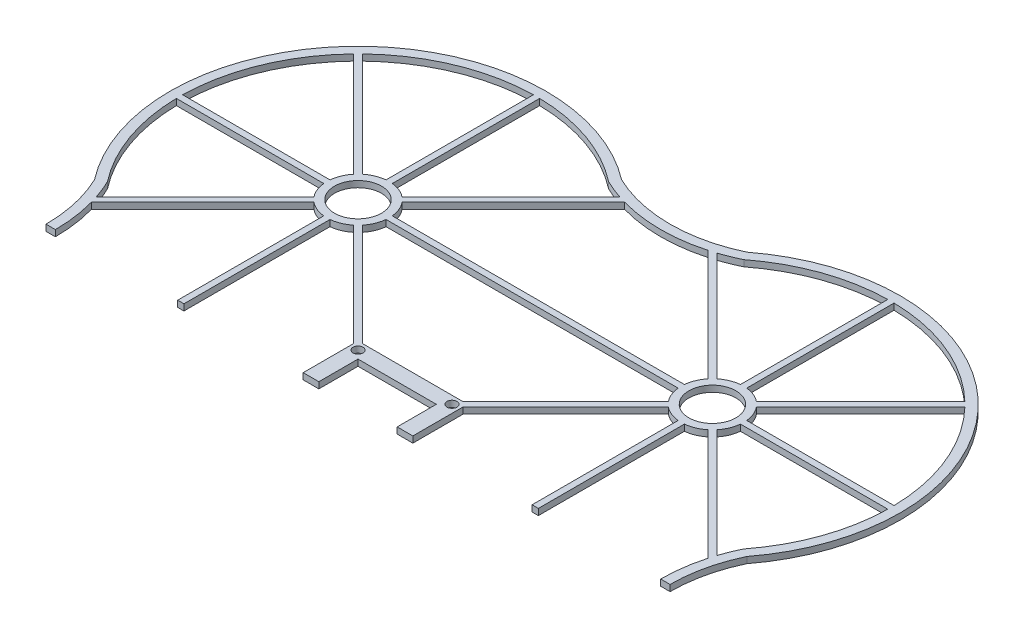
SolidWorks part; units mm, degrees
ref_plane "Front Plane" through (0, 0, 0) normal (0, 0, 1) x (1, 0, 0)
ref_plane "Top Plane" through (0, 0, 0) normal (0, 1, 0) x (1, 0, 0)
ref_plane "Right Plane" through (0, 0, 0) normal (1, 0, 0) x (0, 0, -1)
sketch "Sketch1" plane through (0, 0, 0) normal (0, 1, 0) x (1, 0, 0)
  line L0 (14.1421, 14.1421) -> (15, 15)
  line L1 (-15, -15) -> (-13.3013, -15)
  line L2 (-15, -15) -> (-15, -13.3013)
  line L3 (-15, 15) -> (-13.3013, 15) construction
  line L4 (15, -15) -> (15, -13.3013)
  line L5 (-15, -15) -> (-14.1421, -14.1421) construction
  line L6 (-15, 15) -> (-14.1421, 14.1421) construction
  line L7 (14.1421, -14.1421) -> (15, -15)
  line L8 (-14.1421, -14.1421) -> (-15, -15)
  line L9 (-14.1421, 14.1421) -> (-56.5685, 56.5685)
  line L10 (-104.1368, 20) -> (-104.1368, -20) construction
  line L11 (15, -15) -> (56.5685, -56.5685) construction
  line L12 (-15, -15) -> (-56.5685, -56.5685) construction
  line L13 (15, 15) -> (56.5685, 56.5685) construction
  line L14 (-13.3013, 15) -> (13.3013, 15) construction
  line L15 (13.3013, 15) -> (15, 15)
  line L16 (-14.1421, 14.1421) -> (0, 0) construction
  line L17 (14.1421, -14.1421) -> (15, -15) construction
  line L18 (0, 0) -> (-14.1421, 14.1421) construction
  line L19 (-15, -13.3013) -> (-15, 13.3013) construction
  line L20 (-15, 13.3013) -> (-15, 15)
  line L21 (-14.1421, -14.1421) -> (0, 0) construction
  line L22 (14.1421, 14.1421) -> (15, 15) construction
  line L23 (0, 0) -> (-14.1421, -14.1421) construction
  line L24 (-13.3013, -15) -> (13.3013, -15) construction
  line L25 (13.3013, -15) -> (15, -15)
  line L26 (0, 0) -> (14.1421, -14.1421) construction
  line L27 (0, 0) -> (14.1421, -14.1421) construction
  line L28 (15, -13.3013) -> (15, 13.3013) construction
  line L29 (15, 13.3013) -> (15, 15)
  line L30 (0, 0) -> (14.1421, 14.1421) construction
  line L31 (0, 0) -> (14.1421, 14.1421) construction
  arc A0 (13.3013, 15) -> (15, 13.3013) centre (56.5685, 56.5685) ccw
  arc A1 (76.5685, 0) -> (36.5685, 0) centre (56.5685, -56.5685) ccw construction
  arc A2 (-104.1368, -20) -> (-20, -104.1368) centre (-56.5685, -56.5685) ccw
  arc A3 (-15, 13.3013) -> (-14.1421, 14.1421) centre (-56.5685, 56.5685) ccw
  arc A4 (-104.1368, 20) -> (-104.1368, -20) centre (-146.0012, 0) cw
  arc A5 (20, 104.1368) -> (-20, 104.1368) centre (0, 146.0012) cw
  arc A6 (104.1368, -20) -> (104.1368, 20) centre (146.0012, 0) cw
  arc A7 (-20, -104.1368) -> (20, -104.1368) centre (0, -146.0012) cw
  arc A8 (-76.5685, 0) -> (-36.5685, 0) centre (-56.5685, 56.5685) ccw construction
  arc A9 (-36.5685, 0) -> (-76.5685, 0) centre (-56.5685, -56.5685) ccw construction
  arc A10 (-76.5685, 0) -> (-104.1368, -20) centre (-56.5685, -56.5685) ccw construction
  arc A11 (-104.1368, 20) -> (-76.5685, 0) centre (-56.5685, 56.5685) ccw construction
  arc A12 (0, 76.5685) -> (-20, 104.1368) centre (-56.5685, 56.5685) ccw construction
  arc A13 (-20, 104.1368) -> (-104.1368, 20) centre (-56.5685, 56.5685) ccw
  arc A14 (20, 104.1368) -> (0, 76.5685) centre (56.5685, 56.5685) ccw construction
  arc A15 (0, 36.5685) -> (0, 76.5685) centre (-56.5685, 56.5685) ccw construction
  arc A16 (0, 76.5685) -> (0, 36.5685) centre (56.5685, 56.5685) ccw construction
  arc A17 (76.5685, 0) -> (104.1368, 20) centre (56.5685, 56.5685) ccw construction
  arc A18 (104.1368, 20) -> (20, 104.1368) centre (56.5685, 56.5685) ccw
  arc A19 (104.1368, -20) -> (76.5685, 0) centre (56.5685, -56.5685) ccw construction
  arc A20 (0, -76.5685) -> (20, -104.1368) centre (56.5685, -56.5685) ccw construction
  arc A21 (20, -104.1368) -> (104.1368, -20) centre (56.5685, -56.5685) ccw
  arc A22 (-20, -104.1368) -> (0, -76.5685) centre (-56.5685, -56.5685) ccw construction
  arc A23 (-13.3013, -15) -> (-15, -13.3013) centre (-56.5685, -56.5685) ccw
  arc A24 (0, -36.5685) -> (0, -76.5685) centre (56.5685, -56.5685) ccw construction
  arc A25 (0, -76.5685) -> (0, -36.5685) centre (-56.5685, -56.5685) ccw construction
  arc A26 (13.3013, -15) -> (0, -36.5685) centre (56.5685, -56.5685) ccw construction
  arc A27 (0, -36.5685) -> (-13.3013, -15) centre (-56.5685, -56.5685) ccw construction
  arc A28 (-15, -13.3013) -> (-36.5685, 0) centre (-56.5685, -56.5685) ccw construction
  arc A29 (-36.5685, 0) -> (-15, 13.3013) centre (-56.5685, 56.5685) ccw construction
  arc A30 (36.5685, 0) -> (15, -13.3013) centre (56.5685, -56.5685) ccw construction
  arc A31 (15, -13.3013) -> (13.3013, -15) centre (56.5685, -56.5685) ccw
  arc A32 (15, 13.3013) -> (36.5685, 0) centre (56.5685, 56.5685) ccw construction
  arc A33 (36.5685, 0) -> (76.5685, 0) centre (56.5685, 56.5685) ccw construction
  arc A34 (0, 36.5685) -> (13.3013, 15) centre (56.5685, 56.5685) ccw construction
  arc A35 (-14.1421, 14.1421) -> (-13.3013, 15) centre (-56.5685, 56.5685) ccw construction
  arc A36 (-13.3013, 15) -> (0, 36.5685) centre (-56.5685, 56.5685) ccw construction
  arc A37 (-21.5857, 101.5708) -> (-101.5708, 21.5857) centre (-56.5685, 56.5685) ccw
  arc A38 (-101.5708, 21.5857) -> (-101.5708, -21.5857) centre (-146.0012, 0) cw
  arc A39 (-101.5708, -21.5857) -> (-21.5857, -101.5708) centre (-56.5685, -56.5685) ccw
  arc A40 (-21.5857, -101.5708) -> (21.5857, -101.5708) centre (0, -146.0012) cw
  arc A41 (21.5857, -101.5708) -> (101.5708, -21.5857) centre (56.5685, -56.5685) ccw
  arc A42 (101.5708, -21.5857) -> (101.5708, 21.5857) centre (146.0012, 0) cw
  arc A43 (101.5708, 21.5857) -> (21.5857, 101.5708) centre (56.5685, 56.5685) ccw
  arc A44 (21.5857, 101.5708) -> (-21.5857, 101.5708) centre (0, 146.0012) cw
  point P0 (0, 0)
  point P18 (0, 0)
  point P31 (0, 0)
  point P45 (-266.1251, 102.6457)
  dimension "D1" = 3
  dimension "D7" = 4
extrude "Boss-Extrude1" add sketch "Sketch1" along normal blind 2 contours A7 A21 A6 A18 A5 A13 A4 A2 A44 A43 A42 A41 A40 A39 A38 A37
sketch "Sketch2" plane through (0, 2, 0) normal (0, 1, 0) x (1, 0, 0)
  line L0 (-96.8736, 96.8736) -> (-63.6396, 63.6396)
  line L1 (-15, 15) -> (-13.4, 15)
  line L2 (-15, 15) -> (-15, 13.4)
  line L3 (-15, -15) -> (-13.4, -15)
  line L4 (15, 15) -> (15, 13.4)
  line L5 (-15, 15) -> (15, -15) construction
  line L6 (-15, -15) -> (15, 15) construction
  line L7 (16.0858, -17.5) -> (-16.0858, -17.5)
  line L8 (17.5, -16.0858) -> (17.5, 16.0858)
  line L9 (16.0858, 17.5) -> (-16.0858, 17.5)
  line L10 (-17.5, -16.0858) -> (-17.5, 16.0858)
  line L11 (16.1314, -16.1314) -> (-17.5, 17.5) construction
  line L12 (17.5, 17.5) -> (-17.5, -17.5) construction
  line L13 (12.5, -12.5) -> (-12.5, -12.5)
  line L14 (12.5, -12.5) -> (12.5, 12.5)
  line L15 (12.5, 12.5) -> (-12.5, 12.5)
  line L16 (-12.5, -12.5) -> (-12.5, 12.5)
  line L17 (12.5, -12.5) -> (-12.5, 12.5) construction
  line L18 (12.5, 12.5) -> (-12.5, -12.5) construction
  line L19 (-97.5807, 96.1665) -> (-64.3113, 62.8971)
  line L20 (-96.1665, 97.5807) -> (-62.8971, 64.3113)
  line L21 (-57.5685, 113.5685) -> (-57.5685, 66.5184)
  line L22 (-55.5685, 113.5685) -> (-55.5685, 66.5184)
  line L23 (-15.4636, 99.0877) -> (-50.24, 64.3113)
  line L24 (-13.2952, 98.4277) -> (-48.8258, 62.8971)
  line L25 (0.4315, 57.5685) -> (-46.6187, 57.5685)
  line L26 (0.4315, 55.5685) -> (-46.6187, 55.5685)
  line L27 (-16.0858, 17.5) -> (-48.8258, 50.24)
  line L28 (-17.5, 16.0858) -> (-50.24, 48.8258)
  line L29 (-55.5685, -46.6187) -> (-55.5685, 46.6187)
  line L30 (-57.5685, -46.6187) -> (-57.5685, 46.6187)
  line L31 (-98.4277, 13.2952) -> (-62.8971, 48.8258)
  line L32 (-99.0877, 15.4636) -> (-64.3113, 50.24)
  line L33 (-113.5685, 55.5685) -> (-66.5184, 55.5685)
  line L34 (-113.5685, 57.5685) -> (-66.5184, 57.5685)
  line L35 (55.5685, 113.5685) -> (55.5685, 66.5184)
  line L36 (57.5685, 113.5685) -> (57.5685, 66.5184)
  line L37 (96.1665, 97.5807) -> (62.8971, 64.3113)
  line L38 (97.5807, 96.1665) -> (64.3113, 62.8971)
  line L39 (113.5685, 57.5685) -> (66.5184, 57.5685)
  line L40 (113.5685, 55.5685) -> (66.5184, 55.5685)
  line L41 (99.0877, 15.4636) -> (64.3113, 50.24)
  line L42 (98.4277, 13.2952) -> (62.8971, 48.8258)
  line L43 (15.4636, 99.0877) -> (50.24, 64.3113)
  line L44 (13.2952, 98.4277) -> (48.8258, 62.8971)
  line L45 (-46.5685, 57.5685) -> (46.6187, 57.5685)
  line L46 (-46.5685, 55.5685) -> (46.6187, 55.5685)
  line L47 (16.0858, 17.5) -> (48.8258, 50.24)
  line L48 (17.5, 16.0858) -> (50.24, 48.8258)
  line L49 (55.5685, -46.6187) -> (55.5685, 46.6187)
  line L50 (57.5685, -46.6187) -> (57.5685, 46.6187)
  line L51 (113.5685, -55.5685) -> (66.5184, -55.5685)
  line L52 (113.5685, -57.5685) -> (66.5184, -57.5685)
  line L53 (97.5807, -96.1665) -> (64.3113, -62.8971)
  line L54 (96.1665, -97.5807) -> (62.8971, -64.3113)
  line L55 (57.5685, -113.5685) -> (57.5685, -66.5184)
  line L56 (55.5685, -113.5685) -> (55.5685, -66.5184)
  line L57 (15.4636, -99.0877) -> (50.24, -64.3113)
  line L58 (13.2952, -98.4277) -> (48.8258, -62.8971)
  line L59 (99.0877, -15.4636) -> (64.3113, -50.24)
  line L60 (98.4277, -13.2952) -> (62.8971, -48.8258)
  line L61 (57.5685, 0.4315) -> (57.5685, -46.5685)
  line L62 (55.5685, 0.4315) -> (55.5685, -46.5685)
  line L63 (17.5, -16.0858) -> (50.24, -48.8258)
  line L64 (16.0858, -17.5) -> (48.8258, -50.24)
  line L65 (-46.6187, -55.5685) -> (46.6187, -55.5685)
  line L66 (-46.6187, -57.5685) -> (46.6187, -57.5685)
  line L67 (-55.5685, -113.5685) -> (-55.5685, -66.5184)
  line L68 (-57.5685, -113.5685) -> (-57.5685, -66.5184)
  line L69 (-96.1665, -97.5807) -> (-62.8971, -64.3113)
  line L70 (-97.5807, -96.1665) -> (-64.3113, -62.8971)
  line L71 (-113.5685, -57.5685) -> (-66.5184, -57.5685)
  line L72 (-113.5685, -55.5685) -> (-66.5184, -55.5685)
  line L73 (-99.0877, -15.4636) -> (-64.3113, -50.24)
  line L74 (-98.4277, -13.2952) -> (-62.8971, -48.8258)
  line L75 (-15.4636, -99.0877) -> (-50.24, -64.3113)
  line L76 (-13.2952, -98.4277) -> (-48.8258, -62.8971)
  line L77 (0.4315, -57.5685) -> (-46.5685, -57.5685)
  line L78 (0.4315, -55.5685) -> (-46.5685, -55.5685)
  line L79 (-16.0858, -17.5) -> (-48.8258, -50.24)
  line L80 (-17.5, -16.0858) -> (-50.24, -48.8258)
  line L81 (-55.5685, 0.4315) -> (-55.5685, -46.5685)
  line L82 (-57.5685, 0.4315) -> (-57.5685, -46.5685)
  line L83 (-97.5807, 96.1665) -> (-64.3467, 62.9325) construction
  line L84 (-96.1665, 97.5807) -> (-62.9325, 64.3467) construction
  line L85 (13.4, -15) -> (15, -15)
  line L86 (15, -13.4) -> (15, -15)
  line L87 (13.4, 15) -> (15, 15)
  line L88 (-15, -13.4) -> (-15, -15)
  circle A0 centre (-15, 15) radius 1.6
  circle A1 centre (15, 15) radius 1.6
  circle A2 centre (15, -15) radius 1.6
  circle A3 centre (-15, -15) radius 1.6
  arc A4 (-62.8971, 48.8258) -> (-57.5685, 46.6187) centre (-56.5685, 56.5685) ccw
  arc A5 (-21.5857, 101.5708) -> (-101.5708, 21.5857) centre (-56.5685, 56.5685) ccw construction
  arc A6 (-21.5857, 101.5708) -> (-55.5685, 113.5598) centre (-56.5685, 56.5685) ccw
  arc A7 (50.24, 48.8258) -> (55.5685, 46.6187) centre (56.5685, 56.5685) ccw
  arc A8 (57.5685, -66.5184) -> (62.8971, -64.3113) centre (56.5685, -56.5685) ccw
  arc A9 (-62.8971, -64.3113) -> (-57.5685, -66.5184) centre (-56.5685, -56.5685) ccw
  arc A10 (-21.5857, 101.5708) -> (21.5857, 101.5708) centre (0, 146.0012) ccw construction
  arc A11 (101.5708, 21.5857) -> (21.5857, 101.5708) centre (56.5685, 56.5685) ccw construction
  arc A12 (101.5708, 21.5857) -> (101.5708, -21.5857) centre (146.0012, 0) ccw construction
  arc A13 (21.5857, -101.5708) -> (101.5708, -21.5857) centre (56.5685, -56.5685) ccw construction
  arc A14 (21.5857, -101.5708) -> (-21.5857, -101.5708) centre (0, -146.0012) ccw construction
  arc A15 (-101.5708, -21.5857) -> (-21.5857, -101.5708) centre (-56.5685, -56.5685) ccw construction
  arc A16 (-101.5708, -21.5857) -> (-101.5708, 21.5857) centre (-146.0012, 0) ccw construction
  arc A17 (-21.5857, 101.5708) -> (-15.4636, 99.0877) centre (0, 146.0012) ccw
  arc A18 (20, -104.1368) -> (-20, -104.1368) centre (0, -146.0012) ccw
  arc A19 (20, -104.1368) -> (104.1368, -20) centre (56.5685, -56.5685) ccw
  arc A20 (104.1368, 20) -> (104.1368, -20) centre (146.0012, 0) ccw
  arc A21 (104.1368, 20) -> (20, 104.1368) centre (56.5685, 56.5685) ccw
  arc A22 (-20, 104.1368) -> (20, 104.1368) centre (0, 146.0012) ccw
  arc A23 (-20, 104.1368) -> (-104.1368, 20) centre (-56.5685, 56.5685) ccw
  arc A24 (-104.1368, -20) -> (-104.1368, 20) centre (-146.0012, 0) ccw
  arc A25 (-104.1368, -20) -> (-20, -104.1368) centre (-56.5685, -56.5685) ccw
  arc A26 (20, -104.1368) -> (-20, -104.1368) centre (0, -146.0012) ccw
  arc A27 (20, -104.1368) -> (104.1368, -20) centre (56.5685, -56.5685) ccw
  arc A28 (104.1368, 20) -> (104.1368, -20) centre (146.0012, 0) ccw
  arc A29 (104.1368, 20) -> (20, 104.1368) centre (56.5685, 56.5685) ccw
  arc A30 (-20, 104.1368) -> (20, 104.1368) centre (0, 146.0012) ccw
  arc A31 (-20, 104.1368) -> (-104.1368, 20) centre (-56.5685, 56.5685) ccw
  arc A32 (-104.1368, -20) -> (-104.1368, 20) centre (-146.0012, 0) ccw
  arc A33 (-104.1368, -20) -> (-20, -104.1368) centre (-56.5685, -56.5685) ccw
  arc A34 (101.5708, 21.5857) -> (113.5598, 55.5685) centre (56.5685, 56.5685) ccw
  arc A35 (101.5708, 21.5857) -> (99.0877, 15.4636) centre (146.0012, 0) ccw
  arc A36 (21.5857, -101.5708) -> (55.5685, -113.5598) centre (56.5685, -56.5685) ccw
  arc A37 (21.5857, -101.5708) -> (15.4636, -99.0877) centre (0, -146.0012) ccw
  arc A38 (-101.5708, -21.5857) -> (-113.5598, -55.5685) centre (-56.5685, -56.5685) ccw
  arc A39 (-101.5708, -21.5857) -> (-99.0877, -15.4636) centre (-146.0012, 0) ccw
  circle A40 centre (-56.5685, -56.5685) radius 7.5
  circle A41 centre (-56.5685, 56.5685) radius 7.5
  circle A42 centre (56.5685, 56.5685) radius 7.5
  circle A43 centre (56.5685, -56.5685) radius 7.5
  arc A44 (57.5685, -113.5598) -> (96.1603, -97.5745) centre (56.5685, -56.5685) ccw
  arc A45 (13.2952, -98.4277) -> (-13.2952, -98.4277) centre (0, -146.0012) ccw
  arc A46 (97.5745, -96.1603) -> (113.5598, -57.5685) centre (56.5685, -56.5685) ccw
  arc A47 (-15.4636, -99.0877) -> (-21.5857, -101.5708) centre (0, -146.0012) ccw
  arc A48 (48.8258, -50.24) -> (46.6187, -55.5685) centre (56.5685, -56.5685) ccw
  arc A49 (55.5685, -46.6187) -> (50.24, -48.8258) centre (56.5685, -56.5685) ccw
  arc A50 (50.24, -64.3113) -> (55.5685, -66.5184) centre (56.5685, -56.5685) ccw
  arc A51 (62.8971, -48.8258) -> (57.5685, -46.6187) centre (56.5685, -56.5685) ccw
  arc A52 (46.6187, -57.5685) -> (48.8258, -62.8971) centre (56.5685, -56.5685) ccw
  arc A53 (66.5184, -55.5685) -> (64.3113, -50.24) centre (56.5685, -56.5685) ccw
  arc A54 (64.3113, -62.8971) -> (66.5184, -57.5685) centre (56.5685, -56.5685) ccw
  arc A55 (-55.5685, -66.5184) -> (-50.24, -64.3113) centre (-56.5685, -56.5685) ccw
  arc A56 (-48.8258, -62.8971) -> (-46.6187, -57.5685) centre (-56.5685, -56.5685) ccw
  arc A57 (-46.6187, -55.5685) -> (-48.8258, -50.24) centre (-56.5685, -56.5685) ccw
  arc A58 (-50.24, -48.8258) -> (-55.5685, -46.6187) centre (-56.5685, -56.5685) ccw
  arc A59 (-57.5685, -46.6187) -> (-62.8971, -48.8258) centre (-56.5685, -56.5685) ccw
  arc A60 (-64.3113, -50.24) -> (-66.5184, -55.5685) centre (-56.5685, -56.5685) ccw
  arc A61 (-66.5184, -57.5685) -> (-64.3113, -62.8971) centre (-56.5685, -56.5685) ccw
  arc A62 (113.5598, -55.5685) -> (101.5708, -21.5857) centre (56.5685, -56.5685) ccw
  arc A63 (99.0877, -15.4636) -> (101.5708, -21.5857) centre (146.0012, 0) ccw
  arc A64 (57.5685, 46.6187) -> (62.8971, 48.8258) centre (56.5685, 56.5685) ccw
  arc A65 (46.6187, 55.5685) -> (48.8258, 50.24) centre (56.5685, 56.5685) ccw
  arc A66 (48.8258, 62.8971) -> (46.6187, 57.5685) centre (56.5685, 56.5685) ccw
  arc A67 (55.5685, 66.5184) -> (50.24, 64.3113) centre (56.5685, 56.5685) ccw
  arc A68 (62.8971, 64.3113) -> (57.5685, 66.5184) centre (56.5685, 56.5685) ccw
  arc A69 (66.5184, 57.5685) -> (64.3113, 62.8971) centre (56.5685, 56.5685) ccw
  arc A70 (64.3113, 50.24) -> (66.5184, 55.5685) centre (56.5685, 56.5685) ccw
  arc A71 (98.4277, 13.2952) -> (98.4277, -13.2952) centre (146.0012, 0) ccw
  arc A72 (113.5598, 57.5685) -> (97.5745, 96.1603) centre (56.5685, 56.5685) ccw
  arc A73 (96.1603, 97.5745) -> (57.5685, 113.5598) centre (56.5685, 56.5685) ccw
  arc A74 (55.5685, 113.5598) -> (21.5857, 101.5708) centre (56.5685, 56.5685) ccw
  arc A75 (15.4636, 99.0877) -> (21.5857, 101.5708) centre (0, 146.0012) ccw
  arc A76 (-13.2952, 98.4277) -> (13.2952, 98.4277) centre (0, 146.0012) ccw
  arc A77 (-55.5685, 46.6187) -> (-50.24, 48.8258) centre (-56.5685, 56.5685) ccw
  arc A78 (-48.8258, 50.24) -> (-46.6187, 55.5685) centre (-56.5685, 56.5685) ccw
  arc A79 (-66.5184, 55.5685) -> (-64.3113, 50.24) centre (-56.5685, 56.5685) ccw
  arc A80 (-64.3113, 62.8971) -> (-66.5184, 57.5685) centre (-56.5685, 56.5685) ccw
  arc A81 (-57.5685, 66.5184) -> (-62.8971, 64.3113) centre (-56.5685, 56.5685) ccw
  arc A82 (-50.24, 64.3113) -> (-55.5685, 66.5184) centre (-56.5685, 56.5685) ccw
  arc A83 (-46.6187, 57.5685) -> (-48.8258, 62.8971) centre (-56.5685, 56.5685) ccw
  arc A84 (-57.5685, 113.5598) -> (-96.1603, 97.5745) centre (-56.5685, 56.5685) ccw
  arc A85 (-97.5745, 96.1603) -> (-113.5598, 57.5685) centre (-56.5685, 56.5685) ccw
  arc A86 (-113.5598, 55.5685) -> (-101.5708, 21.5857) centre (-56.5685, 56.5685) ccw
  arc A87 (-99.0877, 15.4636) -> (-101.5708, 21.5857) centre (-146.0012, 0) ccw
  arc A88 (-98.4277, -13.2952) -> (-98.4277, 13.2952) centre (-146.0012, 0) ccw
  arc A89 (-113.5598, -57.5685) -> (-97.5745, -96.1603) centre (-56.5685, -56.5685) ccw
  arc A90 (-96.1603, -97.5745) -> (-57.5685, -113.5598) centre (-56.5685, -56.5685) ccw
  arc A91 (-55.5685, -113.5598) -> (-21.5857, -101.5708) centre (-56.5685, -56.5685) ccw
  point P0 (0, 0)
  point P10 (0, 0)
  point P15 (0, 0)
  point P63 (-56.5685, 56.5685)
  point P166 (0, 0)
  point P193 (0, 0)
  dimension "D3" = 3.2
  dimension "D8" = 20
  dimension "D14" = 15
  dimension "D1" = 30
  dimension "D2" = 30
  dimension "D4" = 35
  dimension "D5" = 35
  dimension "D6" = 25
  dimension "D7" = 25
  dimension "D9" = 1
  dimension "D10" = 1
  dimension "D13" = 0
  dimension "D11" = 8
  dimension "D12" = 4
  dimension "D15" = 4
extrude "Boss-Extrude3" add sketch "Sketch2" against normal blind 2
sketch "Sketch3" plane through (0, 2, 0) normal (0, 1, 0) x (1, 0, 0)
  line L0 (0, 0) -> (161.2109, 0)
  line L1 (161.2109, 0) -> (161.2109, -128.0455)
  line L2 (161.2109, -128.0455) -> (-148.1728, -128.0455)
  line L3 (-148.1728, -128.0455) -> (-148.1728, -116.6001)
  line L4 (0, 0) -> (-171.4213, 0)
  line L5 (-171.4213, 0) -> (-148.1728, -116.6001)
extrude "Cut-Extrude1" cut sketch "Sketch3" against normal mid plane 280
